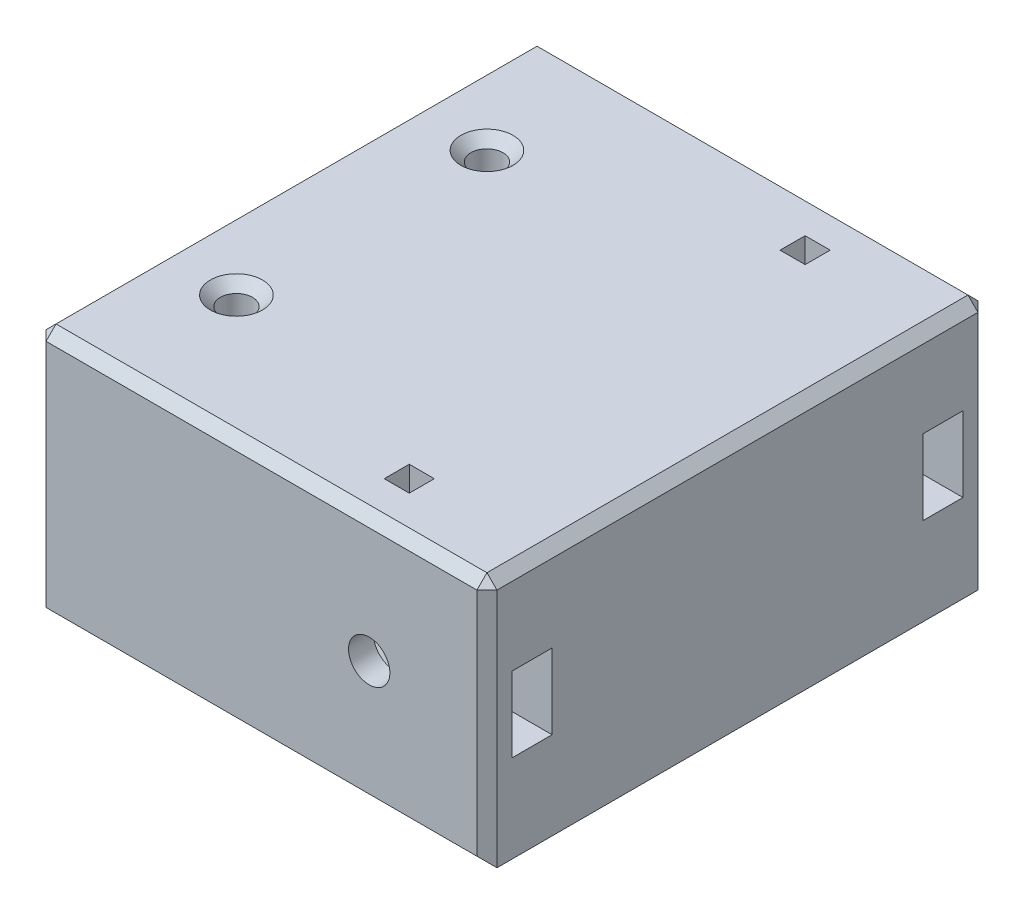
SolidWorks part; units mm, degrees
ref_plane "Front Plane" through (0, 0, 0) normal (1, 0, 0) x (0, 1, 0)
ref_plane "Top Plane" through (0, 0, 0) normal (0, 0, 1) x (0, 1, 0)
ref_plane "Right Plane" through (0, 0, 0) normal (0, 1, 0) x (-1, 0, 0)
sketch "Sketch1" plane through (0, 0, 0) normal (1, 0, 0) x (0, 1, 0)
  line L1 (25, 50) -> (-25, 50)
  line L2 (25, 50) -> (25, -50)
  line L3 (25, -50) -> (-25, -50)
  line L4 (-25, 50) -> (-25, -50)
  line L5 (25, 50) -> (-25, -50) construction
  line L6 (25, -50) -> (-25, 50) construction
  point P0 (0, 0)
  dimension "D1" = 50
  dimension "D2" = 100
extrude "Boss-Extrude1" add sketch "Sketch1" along normal blind 90
sketch "Sketch2" plane through (0, 25, 0) normal (0, 1, 0) x (-1, 0, 0)
  line L0 (-15, 25) -> (-15, -25) construction
  line L1 (0, 0) -> (-15, 0) construction
  line L2 (0, -50) -> (0, 50) construction
  circle A0 centre (-15, -25) radius 3.2
  circle A1 centre (-15, 25) radius 3.2
  point P3 (-15, 0)
  dimension "D3" = 6.4
  dimension "D1" = 15
  dimension "D2" = 50
extrude "Cut-Extrude1" cut sketch "Sketch2" against normal through all both and the other way through all
chamfer "Chamfer1" distance 2 angle 45 14 edges at (0, 25, 0) (45, 25, -50) (0, 0, 50) (45, 25, 50) (45, -25, 50) (90, 0, 50) (90, 25, 0) (0, 0, -50) (45, -25, -50) (90, 0, -50) (15, -25, -21.8) (15, -25, 21.8)
sketch "Sketch3" plane through (0, 0, 50) normal (0, 0, 1) x (1, 0, 0)
  line L0 (88, 23) -> (45, -23) construction
  line L1 (2, -23) -> (88, -23) construction
  line L2 (72.9952, 3.75) -> (66.5, 7.5)
  line L3 (66.5, 7.5) -> (60.0048, 3.75)
  line L4 (60.0048, 3.75) -> (60.0048, -3.75)
  line L5 (60.0048, -3.75) -> (66.5, -7.5)
  line L6 (66.5, -7.5) -> (72.9952, -3.75)
  line L7 (72.9952, -3.75) -> (72.9952, 3.75)
  line L8 (116.1119, -7.5) -> (16.8881, -7.5)
  line L9 (116.1119, -7.5) -> (116.1119, 7.5)
  line L10 (116.1119, 7.5) -> (16.8881, 7.5)
  line L11 (16.8881, -7.5) -> (16.8881, 7.5)
  line L12 (116.1119, -7.5) -> (16.8881, 7.5) construction
  line L13 (116.1119, 7.5) -> (16.8881, -7.5) construction
  circle A0 centre (66.5, 0) radius 6.4952 construction
  point P16 (0, 0)
  point P17 (31.6002, -23)
  point P20 (35.6785, -23)
  point P21 (30, -23)
  line M14 (88, -23) -> (88, 23)
  dimension "D1" = 15
extrude "Cut-Extrude2" cut sketch "Sketch3" against normal blind 8 from offset 5 contours L10 L2 L7 L6 L8 M14 | L9 L10 L8 M14 | L6 L7 L2 L3 L4 L5 offset against normal yes
sketch "Sketch4" plane through (0, 0, 50) normal (0, 0, 1) x (1, 0, 0)
  circle A0 centre (66.5, 0) radius 4.125
  dimension "D1" = 8.25
extrude "Cut-Extrude3" cut sketch "Sketch4" against normal blind 8
sketch "Sketch6" plane through (0, 7.5, 0) normal (0, -1, 0) x (1, 0, 0)
  line L1 (61.5, 42) -> (71.5, 42)
  line L2 (61.5, 42) -> (61.5, 37)
  line L3 (61.5, 37) -> (71.5, 37)
  line L4 (90, 45) -> (66.5, 45)
  line L5 (66.5, 45) -> (66.5, 37)
  line L6 (66.5, 37) -> (90, 37)
  line L8 (90, 45) -> (66.5, 45)
  line L10 (66.5, 37) -> (90, 37)
  line L12 (71.5, 42) -> (71.5, 37)
  line L13 (61.5, 42) -> (71.5, 37) construction
  line L14 (61.5, 37) -> (71.5, 42) construction
  line L22 (66.5, 45) -> (66.5, 37)
  line L24 (90, 37) -> (90, 45)
  line L25 (90, 37) -> (90, 45)
  point P2 (66.5, 39.5)
  point P9 (44.9423, 39.5)
  point P10 (0, 0)
  point P11 (0, 0)
  line M8 (66.5, 45) -> (66.5, 37)
  dimension "D2" = 5
  dimension "D3" = 10
  dimension "D1" = 0
extrude "Cut-Extrude4" cut sketch "Sketch6" against normal through all both and the other way through all contours L2 L3 L1 M8
mirror "Mirror1" about plane through (0, 0, 0) normal (0, 0, 1) of "Cut-Extrude2", "Cut-Extrude3", "Cut-Extrude4"
